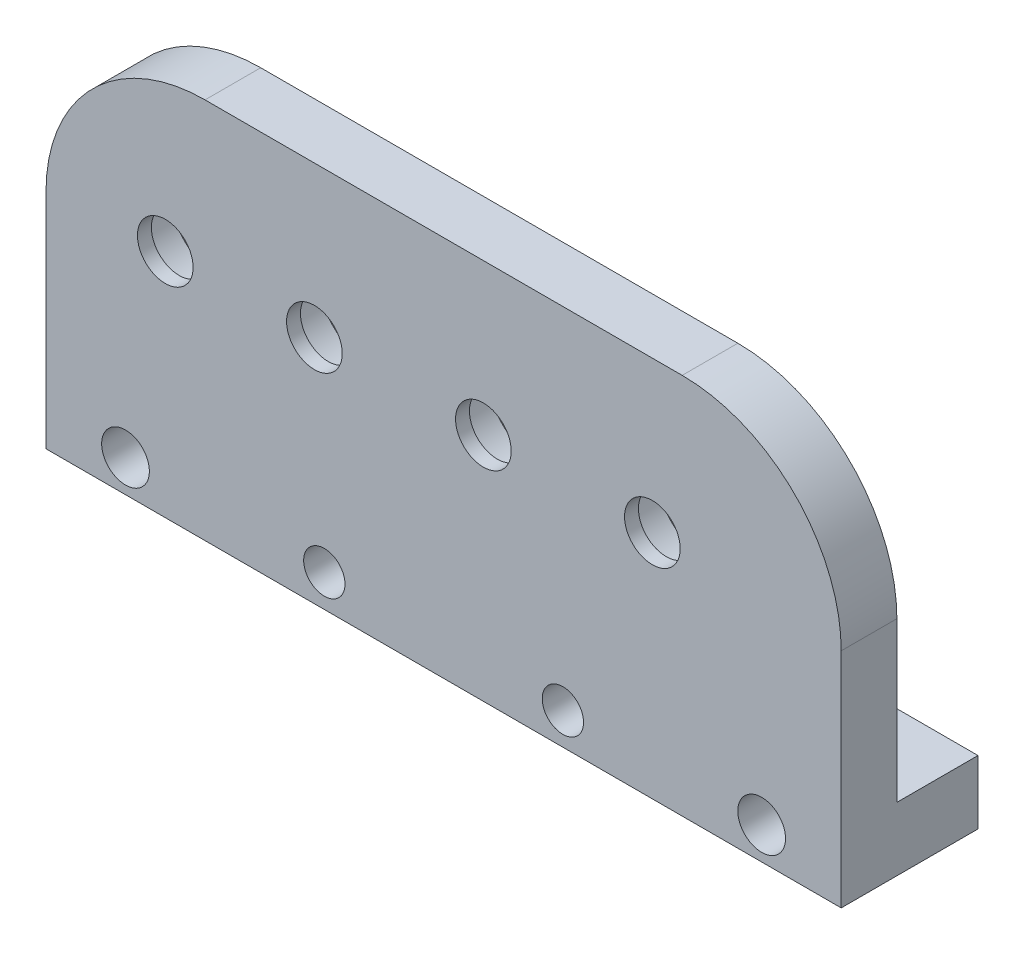
SolidWorks part; units mm, degrees
ref_plane "Front Plane" through (0, 0, 0) normal (0, 0, 1) x (1, 0, 0)
ref_plane "Top Plane" through (0, 0, 0) normal (0, 1, 0) x (1, 0, 0)
ref_plane "Right Plane" through (0, 0, 0) normal (1, 0, 0) x (0, 0, -1)
sketch "Sketch1" plane through (0, 0, 0) normal (0, 0, 1) x (1, 0, 0)
  line L1 (0, 0) -> (100, 0)
  line L2 (0, 0) -> (0, 48)
  line L3 (0, 48) -> (100, 48)
  line L4 (100, 0) -> (100, 48)
  dimension "D1" = 100
  dimension "D2" = 48
extrude "Boss-Extrude1" add sketch "Sketch1" along normal blind 7
sketch "Sketch2" plane through (0, 0, 7) normal (0, 0, 1) x (1, 0, 0)
  line L0 (0, 0) -> (100, 0) construction
  line L1 (0, 48) -> (0, 0) construction
  circle A0 centre (15, 29) radius 3.5
  circle A1 centre (33.75, 29) radius 3.5
  circle A2 centre (55, 29) radius 3.5
  circle A3 centre (76.25, 29) radius 3.5
  dimension "D1" = 7
  dimension "D2" = 18.75
  dimension "D3" = 21.25
  dimension "D4" = 21.25
  dimension "D5" = 29
  dimension "D6" = 15
extrude "Cut-Extrude1" cut sketch "Sketch2" against normal up to next
sketch "Sketch3" plane through (0, 0, 0) normal (0, 0, -1) x (-1, 0, 0)
  line L0 (0, 48) -> (0, 0) construction
  line L1 (-100, 0) -> (0, 0)
  line L2 (-100, 0) -> (-100, 8)
  line L3 (-100, 8) -> (0, 8)
  line L4 (0, 0) -> (0, 8)
  dimension "D1" = 8
extrude "Boss-Extrude2" add sketch "Sketch3" along normal blind 10.2
sketch "Sketch4" plane through (0, 0, 0) normal (0, 0, -1) x (-1, 0, 0)
  circle A0 centre (-76.25, 29) radius 6.55
  circle A1 centre (-55, 29) radius 6.55
  circle A2 centre (-33.75, 29) radius 6.55
  circle A3 centre (-15, 29) radius 6.55
  dimension "D1" = 13.1
extrude "Cut-Extrude2" cut sketch "Sketch4" against normal blind 5.25
sketch "Sketch5" plane through (0, 0, 7) normal (0, 0, 1) x (1, 0, 0)
  line L0 (35, 4.0521) -> (65, 4) construction
  line L1 (0, 0) -> (100, 0) construction
  circle A0 centre (35, 4.0521) radius 2.6
  circle A1 centre (65, 4) radius 2.6
  point P6 (50, 0)
  point P7 (50, 4.0261)
  dimension "D1" = 5.2
  dimension "D2" = 30
  dimension "D3" = 4
extrude "Cut-Extrude3" cut sketch "Sketch5" against normal blind 7
sketch "Sketch7" plane through (0, 0, 0) normal (0, 0, 1) x (1, 0, 0)
  circle A0 centre (35, 4.0521) radius 1.7
  circle A1 centre (65, 4) radius 1.7
  dimension "D1" = 3.4
extrude "Cut-Extrude4" cut sketch "Sketch7" against normal through all
sketch "Sketch8" plane through (0, 0, 7) normal (0, 0, 1) x (1, 0, 0)
  line L0 (10, 4.0521) -> (35, 4.0521) construction
  line L1 (0, 48) -> (0, 0) construction
  line L2 (100, 0) -> (100, 48) construction
  circle A0 centre (10, 4.0521) radius 1.7
  circle A1 centre (90, 4.0521) radius 1.7
  dimension "D1" = 3.4
  dimension "D2" = 10
  dimension "D3" = 10
extrude "Cut-Extrude5" cut sketch "Sketch8" against normal up to next
sketch "Sketch9" plane through (0, 0, 7) normal (0, 0, 1) x (1, 0, 0)
  circle A0 centre (10, 4.0521) radius 3
  circle A1 centre (90, 4.0521) radius 3
  dimension "D1" = 6
extrude "Cut-Extrude6" cut sketch "Sketch9" against normal blind 10
fillet "Fillet1" radius 20 2 edges at (100, 48, 3.5) (0, 48, 3.5)
